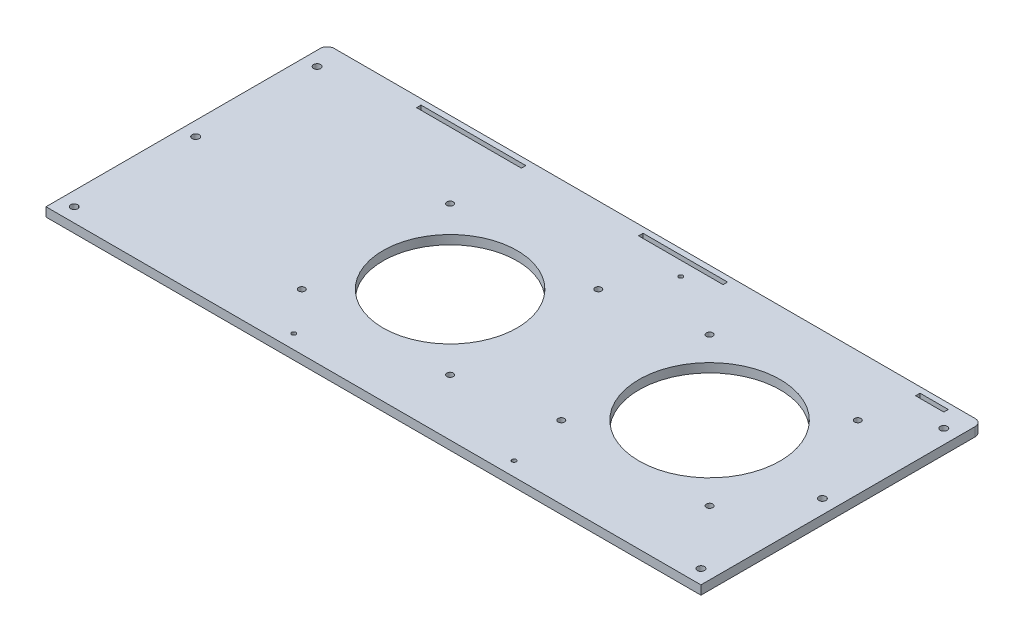
SolidWorks part; units mm, degrees
ref_plane "Front Plane" through (0, 0, 0) normal (0, 0, 1) x (1, 0, 0)
ref_plane "Top Plane" through (0, 0, 0) normal (0, 1, 0) x (1, 0, 0)
ref_plane "Right Plane" through (0, 0, 0) normal (1, 0, 0) x (0, 0, -1)
sketch "Sketch1" plane through (0, 60, 0) normal (0, 1, 0) x (1, 0, 0)
  line L1 (-20.2, 0) -> (443.68, 0)
  line L2 (-20.2, 0) -> (-20.2, -192)
  line L3 (-20.2, -192) -> (443.68, -192)
  line L4 (443.68, 0) -> (443.68, -192)
extrude "Boss-Extrude1" add sketch "Sketch1" along normal up to vertex (6.35 mm away)
sketch "Sketch4" plane through (0, 66.35, 0) normal (0, 1, 0) x (1, 0, 0)
  circle A0 centre (433.68, -10) radius 2.5 construction
  circle A1 centre (433.68, -96) radius 2.5 construction
  circle A2 centre (433.68, -182) radius 2.5 construction
  circle A3 centre (-10.2, -182) radius 2.5 construction
  circle A4 centre (-10.2, -96) radius 2.5 construction
  circle A5 centre (-10.2, -10) radius 2.5 construction
  circle A6 centre (433.68, -10) radius 2.5
  circle A7 centre (433.68, -96) radius 2.5
  circle A8 centre (433.68, -182) radius 2.5
  circle A9 centre (-10.2, -182) radius 2.5
  circle A10 centre (-10.2, -96) radius 2.5
  circle A11 centre (-10.2, -10) radius 2.5
extrude "Cut-Extrude2" cut sketch "Sketch4" against normal through all
sketch "Sketch2" plane through (0, 66.35, 0) normal (0, 1, 0) x (1, 0, 0)
  line L0 (51.05, 3.175) -> (123.7, 3.175) construction
  line L1 (-20.2, 7.175) -> (443.68, 7.175)
  line L2 (-20.2, 7.175) -> (-20.2, 0)
  line L3 (-20.2, 0) -> (443.68, 0)
  line L4 (443.68, 7.175) -> (443.68, 0)
  dimension "D1" = 4
extrude "Boss-Extrude2" add sketch "Sketch2" against normal up to surface (6.35 mm away) up to face at (-10.2, 60, 12.5)
sketch "Sketch3" plane through (0, 66.35, 0) normal (0, 1, 0) x (1, 0, 0)
  line L24 (-201402.0628, 3.175) -> (248597.9372, 3.175) construction
  line L25 (50.25, 0) -> (124.5, 0)
  line L26 (50.25, 0) -> (50.25, 3.175)
  line L27 (50.25, 3.175) -> (124.5, 3.175)
  line L28 (124.5, 0) -> (124.5, 3.175)
  line L29 (87.375, 3.175) -> (87.375, 0) construction
  line L30 (50.25, 1.5875) -> (124.5, 1.5875) construction
  line L31 (207.5, 0) -> (267.37, 0)
  line L32 (207.5, 0) -> (207.5, 3.175)
  line L33 (207.5, 3.175) -> (267.37, 3.175)
  line L34 (267.37, 0) -> (267.37, 3.175)
  line L35 (237.435, 3.175) -> (237.435, 0) construction
  line L36 (207.5, 1.5875) -> (267.37, 1.5875) construction
  line L37 (403.68, 0) -> (423.68, 0)
  line L38 (403.68, 0) -> (403.68, 3.175)
  line L39 (403.68, 3.175) -> (423.68, 3.175)
  line L40 (423.68, 0) -> (423.68, 3.175)
  line L41 (413.68, 3.175) -> (413.68, 0) construction
  line L42 (403.68, 1.5875) -> (423.68, 1.5875) construction
  line L43 (-202523.6313, 0) -> (323657.9361, 0) construction
  point P0 (87.375, 1.5875)
  point P4 (237.435, 1.5875)
  point P8 (413.68, 1.5875)
extrude "Cut-Extrude1" cut sketch "Sketch3" against normal through all
sketch "Sketch5" plane through (0, 66.35, 0) normal (0, 1, 0) x (1, 0, 0)
  line L0 (-202523.6313, 0) -> (323657.9361, 0) construction
  line L1 (-0.2, -182) -> (141.0933, -182) construction
  line L2 (141.0933, -182) -> (282.3867, -182) construction
  circle A0 centre (247.37, -10) radius 1.5
  circle A1 centre (145.287, -182) radius 1.5
  circle A2 centre (301.287, -182) radius 1.5
  dimension "D1" = 3
  dimension "D2" = 10
extrude "Cut-Extrude3" cut sketch "Sketch5" against normal through all
fillet "Fillet1" radius 5 2 edges at (-20.2, 63.175, -7.175) (443.68, 63.175, -7.175)
sketch "Sketch6" plane through (0, 66.35, 0) normal (0, 1, 0) x (1, 0, 0)
  line L1 (121, -152) -> (226, -152) construction
  line L2 (121, -152) -> (121, -47) construction
  line L3 (121, -47) -> (226, -47) construction
  line L4 (226, -152) -> (226, -47) construction
  line L5 (173.5, -47) -> (173.5, -152) construction
  line L6 (121, -99.5) -> (226, -99.5) construction
  line L7 (293.24, -140.45) -> (398.24, -140.45) construction
  line L8 (293.24, -140.45) -> (293.24, -35.45) construction
  line L9 (293.24, -35.45) -> (398.24, -35.45) construction
  line L10 (398.24, -140.45) -> (398.24, -35.45) construction
  line L11 (345.74, -35.45) -> (345.74, -140.45) construction
  line L12 (293.24, -87.95) -> (398.24, -87.95) construction
  circle A0 centre (173.5, -99.5) radius 47.5
  circle A1 centre (345.74, -87.95) radius 50
  circle A2 centre (121, -47) radius 2.25
  circle A3 centre (226, -47) radius 2.25
  circle A4 centre (226, -152) radius 2.25
  circle A5 centre (121, -152) radius 2.25
  circle A6 centre (293.24, -140.45) radius 2.25
  circle A7 centre (293.24, -35.45) radius 2.25
  circle A8 centre (398.24, -35.45) radius 2.25
  circle A9 centre (398.24, -140.45) radius 2.25
  dimension "D1" = 95
  dimension "D2" = 100
  dimension "D3" = 4.5
  dimension "D4" = 105
extrude "Cut-Extrude4" cut sketch "Sketch6" against normal through all
